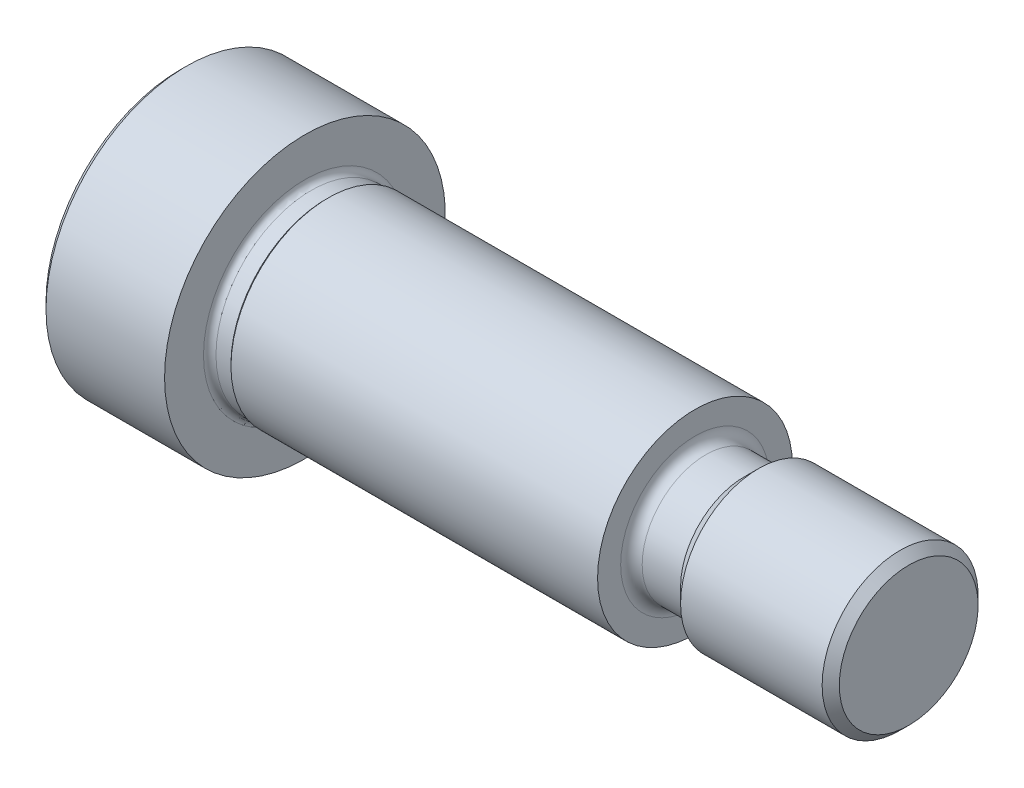
SolidWorks part; units mm, degrees
ref_plane "Plane1" through (0, 0, 0) normal (0, 0, 1) x (1, 0, 0)
ref_plane "Plane2" through (0, 0, 0) normal (0, 1, 0) x (1, 0, 0)
ref_plane "Plane3" through (0, 0, 0) normal (1, 0, 0) x (0, 0, -1)
sketch "BodySke" plane through (0, 0, 0) normal (0, 0, 1) x (1, 0, 0)
  line L0 (0, 0) -> (0, 18)
  line L2 (0, 18) -> (16, 18)
  line L3 (16, 18) -> (16, 13.01)
  line L4 (16.8, 12.21) -> (18.72, 12.21)
  line L5 (18.72, 12.21) -> (19, 12.49)
  line L6 (19, 12.49) -> (66, 12.49)
  line L7 (66, 12.49) -> (66, 9.53)
  line L8 (67.38, 8.15) -> (72.3, 8.15)
  line L9 (72.3, 8.15) -> (74.15, 10)
  line L10 (74.15, 10) -> (92.2985, 10)
  line L11 (92.2985, 10) -> (93.4, 8.8985)
  line L12 (93.4, 8.8985) -> (93.4, 0)
  line L13 (93.4, 0) -> (0, 0)
  line L14 (-6.35, 0) -> (107.95, 0) construction
  line L15 (92.2985, -10) -> (93.4, -8.8985) construction
  line L16 (66, -8.15) -> (72.3, -8.15) construction
  line L17 (19, -12.49) -> (66, -12.49) construction
  line L18 (16, -12.21) -> (18.72, -12.21) construction
  line L20 (74.8, 13.0014) -> (74.8, -4.3514) construction
  line L21 (70.54, 12.6746) -> (70.54, -3.175) construction
  arc A0 (66, 9.53) -> (67.38, 8.15) centre (67.38, 9.53) ccw
  arc A1 (16.8, 12.21) -> (16, 13.01) centre (16.8, 13.01) cw
  point P29 (66, 8.15)
  point P32 (16, 12.21)
  dimension "Thread_neck_fillet_rad" = 1.38
  dimension "Head_fillet_radius" = 0.8
  dimension "Head_ht" = 16
  dimension "Shoulder_neck_dia" = 24.42
  dimension "Diameter" = 24.98
  dimension "Thread_dia" = 20
  dimension "Minor_dia" = 17.797
  dimension "Thread_ch_ang" = 45
  dimension "Thread_neck_dia" = 16.3
  dimension "D11" = 45
  dimension "Thread_length" = 27.4
  dimension "D13" = 45
  dimension "Length" = 50
  dimension "Thread_neck_width" = 6.3
  dimension "Shoulder_neck_width" = 3
  dimension "Thread_nom" = 22.86
  dimension "Advance" = 2.5
  dimension "Thread_lim" = 18.6
  dimension "Head_dia" = 36
revolve "BaseBody" add sketch "BodySke" angle 360 about L14
cosmetic thread "ThreadCosmetic" [suppressed] parameters "Thread_length"=18.6, "Thread_minor"=17.797
chamfer "Chamfer1" distance 0.8 1 edges at (0, 0, 18)
sketch "Sketch2" plane through (0, 0, 0) normal (0, 0, 1) x (1, 0, 0)
  line L0 (0, 6) -> (10, 6)
  line L1 (10, 6) -> (13.4641, 0)
  line L3 (13.4641, 0) -> (0, 0)
  line L4 (0, 0) -> (0, 6)
  line L5 (0, -6) -> (10, -6) construction
  line L6 (0, 0) -> (47.625, 0) construction
  dimension "D2" = 60
  dimension "PreBroach_depth" = 10
  dimension "PreBroach_dia" = 12
revolve "PreBroach" cut sketch "Sketch2" angle 360 about L6
sketch "Sketch3" plane through (0, 0, 0) normal (-1, 0, 0) x (0, 0, 1)
  line L0 (-6, -3.4641) -> (-6, 3.4641)
  line L1 (-6, 3.4641) -> (0, 6.9282)
  line L2 (0, 6.9282) -> (6, 3.4641)
  line L3 (6, 3.4641) -> (6, -3.4641)
  line L4 (6, -3.4641) -> (0, -6.9282)
  line L5 (0, -6.9282) -> (-6, -3.4641)
  dimension "Hex_size" = 12
  dimension "D1" = 6
  dimension "D2" = 6
  dimension "D3" = 120
  dimension "D4" = 12
extrude "Hex" cut sketch "Sketch3" against normal blind 10
sketch "ThdSchSke" plane through (0, 0, 0) normal (0, 0, 1) x (1, 0, 0)
  line L0 (74.8, -8.8985) -> (72.2852, -12.49)
  line L1 (74.8, -8.8985) -> (77.3148, -12.49)
  line L2 (77.3148, -12.49) -> (77.3148, -15.6125)
  line L3 (-3.175, 0) -> (5.1513, 0) construction
  line L5 (77.3148, -15.6125) -> (72.2852, -15.6125)
  line L6 (72.2852, -15.6125) -> (72.2852, -12.49)
  dimension "Thread_minor" = 17.797
  dimension "Diameter" = 24.98
  dimension "SideAngle" = 55
  dimension "VeeAngle" = 70
  dimension "Overcut" = 31.225
  dimension "Start" = 74.8
revolve "ThreadSchematic" [suppressed] cut sketch "ThdSchSke" angle 360 about L3
pattern_linear "ThdSchPat" [suppressed]
equation "\"Thread_minor@ThreadCosmetic\" = \"Minor_dia@BodySke\""
equation "\"D1@Sketch3\" = \"Hex_size@Sketch3\" / 2"
equation "\"D2@Sketch3\" = \"D1@Sketch3\""
equation "\"D4@Sketch3\" = \"Hex_size@Sketch3\""
equation "\"Width@Chamfer1\" = \"Head_fillet_radius@BodySke\""
equation "\"Thread_length@ThreadCosmetic\" = ((sgn( (\"Thread_length@BodySke\" - \"Advance@BodySke\" - \"Thread_neck_width@BodySke\" ) - \"Thread_nom@BodySke\" )-1)*( (\"Thread_length@BodySke\" - \"Advance@BodySke\" - \"Thread_neck_width@BodySke\" ) - \"Thread_nom@BodySke\" ))/-2+ \"Thread_nom@BodySke\""
equation "\"Thread_minor@ThdSchSke\" = \"Minor_dia@BodySke\""
equation "\"Diameter@ThdSchSke\" = \"Diameter@BodySke\""
equation "\"Overcut@ThdSchSke\" = \"Diameter@BodySke\" * 1.25"
equation "\"Start@ThdSchSke\" = \"Head_ht@BodySke\" + \"Length@BodySke\" + \"Thread_length@BodySke\" -  \"Thread_length@ThreadCosmetic\"  '---Non-countersunk---"
equation "\"Num_threads@ThdSchPat\" = int( \"Thread_length@ThreadCosmetic\" / \"Advance@BodySke\" + 0.999 ) + 1"
equation "\"Advance@ThdSchPat\" = \"Thread_length@ThreadCosmetic\" /  (\"Num_threads@ThdSchPat\" - 1) 'relax it"
equation "\"Num_threads@ThdSchPat\" = \"Num_threads@ThdSchPat\" - sgn( \"Num_threads@ThdSchPat\" - 1) '---chamfered tips only---"
